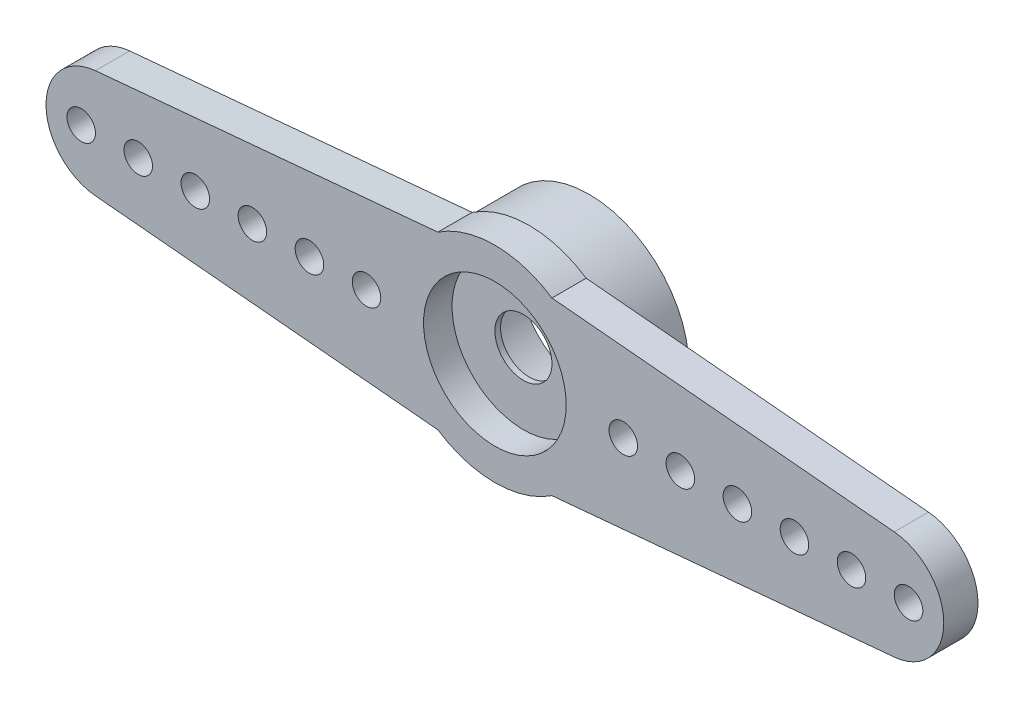
SolidWorks part; units mm, degrees
ref_plane "Front Plane" through (0, 0, 0) normal (0, 0, 1) x (1, 0, 0)
ref_plane "Top Plane" through (0, 0, 0) normal (0, 1, 0) x (1, 0, 0)
ref_plane "Right Plane" through (0, 0, 0) normal (1, 0, 0) x (0, 0, -1)
sketch "Sketch1" plane through (0, 0, 0) normal (0, 0, 1) x (1, 0, 0)
  line L0 (2, 0) -> (14, 0) construction
  line L2 (-2, -6.75) -> (-2, -3)
  line L4 (2, -6.75) -> (2, -3)
  line L5 (-2, -6.75) -> (2, 6.75) construction
  line L6 (-2, 6.75) -> (2, -6.75) construction
  line L7 (2, 0) -> (2, 3) construction
  line L8 (2, 0) -> (2, -3) construction
  line L9 (14, 0) -> (14, 1.9) construction
  line L10 (14, 0) -> (14, -1.9) construction
  line L11 (2, 3) -> (14, 1.9)
  line L12 (14, -1.9) -> (2, -3)
  line L13 (2, 3) -> (2, 6.75)
  line L14 (-2, 0) -> (-2, 3) construction
  line L15 (-2, 0) -> (-2, -3) construction
  line L16 (-2, 0) -> (-14, 0) construction
  line L17 (-14, 0) -> (-14, 1.9) construction
  line L18 (-14, 0) -> (-14, -1.9) construction
  line L19 (-14, 1.9) -> (-2, 3)
  line L20 (-14, -1.9) -> (-2, -3)
  line L21 (-2, 3) -> (-2, 6.75)
  arc A0 (-2, 6.75) -> (2, 6.75) centre (0, 6.75) cw
  arc A1 (2, -6.75) -> (-2, -6.75) centre (0, -6.75) cw
  arc A2 (14, -1.9) -> (14, 1.9) centre (13.8258, 0) ccw
  arc A3 (-14, 1.9) -> (-14, -1.9) centre (-13.8258, 0) ccw
  point P0 (0, 0)
  dimension "D1" = 4
  dimension "D2" = 13.5
  dimension "D3" = 12
  dimension "D4" = 3
  dimension "D5" = 3
  dimension "D6" = 1.9
  dimension "D7" = 1.9
  dimension "D8" = 3
  dimension "D9" = 3
  dimension "D10" = 12
  dimension "D11" = 1.9
  dimension "D12" = 1.9
extrude "Boss-Extrude1" add sketch "Sketch1" along normal blind 1.2
sketch "Sketch2" plane through (0, 0, 0) normal (0, 0, -1) x (-1, 0, 0)
  line L0 (-2, 3) -> (-2, -3) construction
  line L1 (2, -3) -> (2, 3) construction
  line L2 (2, 0) -> (-2, 0) construction
  circle A0 centre (0, 0) radius 3.5
  dimension "D1" = 7
extrude "Boss-Extrude2" add sketch "Sketch2" along normal blind 2.1
sketch "Sketch3" plane through (0, 0, 1.2) normal (0, 0, 1) x (1, 0, 0)
  line L0 (-2, 3) -> (-2, -3) construction
  line L1 (2, -3) -> (2, 3) construction
  line L2 (2, 0) -> (-2, 0) construction
  circle A0 centre (0, 0) radius 2.5
  dimension "D1" = 5
extrude "Cut-Extrude1" cut sketch "Sketch3" against normal blind 1
sketch "Sketch4" plane through (0, 0, 0.2) normal (0, 0, 1) x (1, 0, 0)
  circle A0 centre (0, 0) radius 1
  dimension "D1" = 2
extrude "Cut-Extrude2" cut sketch "Sketch4" against normal through all
sketch "Sketch6" plane through (0, 0, -2.1) normal (0, 0, -1) x (-1, 0, 0)
  circle A0 centre (0, 0) radius 2.45
  dimension "D1" = 4.9
extrude "Cut-Extrude3" cut sketch "Sketch6" against normal blind 2.1
sketch "Sketch7" plane through (0, 0, 1.2) normal (0, 0, 1) x (1, 0, 0)
  line L0 (0, 4.5) -> (0, -4.5) construction
  line L1 (0, -4.5) -> (0, -6.5) construction
  line L2 (0, 0) -> (-0.6381, 0) construction
  line L3 (0, 4.5) -> (0, 6.5) construction
  circle A0 centre (0, -4.5) radius 0.5
  circle A1 centre (0, -6.5) radius 0.5
  circle A2 centre (0, 4.5) radius 0.5
  circle A3 centre (0, 6.5) radius 0.5
  dimension "D3" = 1
  dimension "D4" = 1
  dimension "D5" = 1
  dimension "D6" = 1
  dimension "D1" = 4.5
  dimension "D2" = 2
extrude "Cut-Extrude4" cut sketch "Sketch7" against normal through all
sketch "Sketch8" plane through (0, 0, 1.2) normal (0, 0, 1) x (1, 0, 0)
  line L0 (4.5, 0) -> (-4.5, 0) construction
  line L1 (-4.5, 0) -> (-6.5, 0) construction
  line L2 (-6.5, 0) -> (-8.5, 0) construction
  line L3 (-8.5, 0) -> (-10.5, 0) construction
  line L4 (-10.5, 0) -> (-12.5, 0) construction
  line L5 (-12.5, 0) -> (-14.5, 0) construction
  line L6 (0, 0) -> (0, -0.466) construction
  line L7 (12.5, 0) -> (14.5, 0) construction
  line L8 (10.5, 0) -> (12.5, 0) construction
  line L9 (8.5, 0) -> (10.5, 0) construction
  line L10 (6.5, 0) -> (8.5, 0) construction
  line L11 (4.5, 0) -> (6.5, 0) construction
  circle A0 centre (-4.5, 0) radius 0.5
  circle A1 centre (-6.5, 0) radius 0.5
  circle A2 centre (-8.5, 0) radius 0.5
  circle A3 centre (-10.5, 0) radius 0.5
  circle A4 centre (-12.5, 0) radius 0.5
  circle A5 centre (-14.5, 0) radius 0.5
  circle A6 centre (4.5, 0) radius 0.5
  circle A7 centre (6.5, 0) radius 0.5
  circle A8 centre (8.5, 0) radius 0.5
  circle A9 centre (10.5, 0) radius 0.5
  circle A10 centre (12.5, 0) radius 0.5
  circle A11 centre (14.5, 0) radius 0.5
  dimension "D7" = 1
  dimension "D8" = 1
  dimension "D9" = 1
  dimension "D10" = 1
  dimension "D11" = 1
  dimension "D12" = 1
  dimension "D1" = 4.5
  dimension "D2" = 2
  dimension "D3" = 2
  dimension "D4" = 2
  dimension "D5" = 2
  dimension "D6" = 2
extrude "Cut-Extrude5" cut sketch "Sketch8" against normal through all
sketch "Sketch10" plane through (0, 0, 0) normal (0, 0, -1) x (-1, 0, 0)
  line L0 (2, 6.75) -> (2, 3) construction
  line L1 (14, -1.9) -> (2, -3) construction
  line L2 (-2, 3) -> (-3.5, 8.058)
  line L3 (-3.5, 8.058) -> (0.4107, 10.2637)
  line L4 (0.4107, 10.2637) -> (4.9724, 6.3286)
  line L5 (4.9724, 6.3286) -> (2, 3)
  line L6 (-2, -3) -> (-3.7991, -6.6528)
  line L7 (-3.7991, -6.6528) -> (-0.6308, -10.284)
  line L8 (-0.6308, -10.284) -> (2.5658, -9.7876)
  line L9 (2.5658, -9.7876) -> (3.7316, -4.8264)
  line L10 (3.7316, -4.8264) -> (2, -3)
  arc A0 (-2, 3) -> (2, 3) centre (0, 0) cw
  arc A1 (-2, -3) -> (2, -3) centre (0, 0) ccw
extrude "Cut-Extrude6" cut sketch "Sketch10" against normal blind 10
sketch "Sketch11" plane through (0, 0, 1.2) normal (0, 0, 1) x (1, 0, 0)
